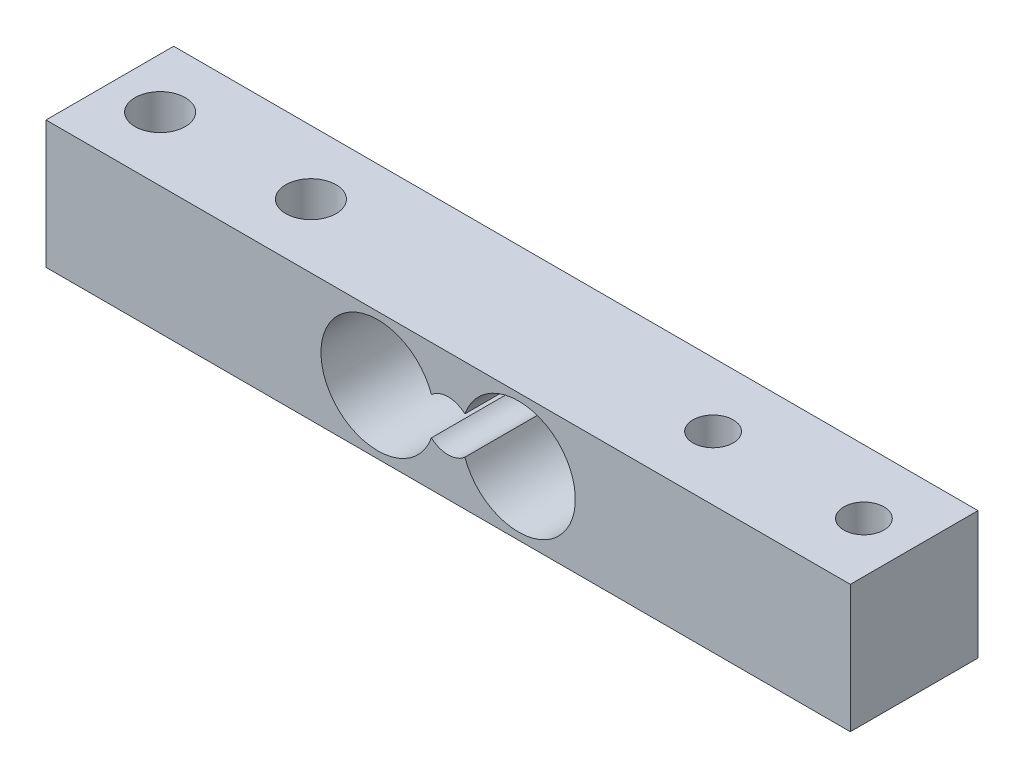
SolidWorks part; units mm, degrees
ref_plane "Front" through (0, 0, 0) normal (0, 0, 1) x (1, 0, 0)
ref_plane "Top" through (0, 0, 0) normal (0, 1, 0) x (1, 0, 0)
ref_plane "Right" through (0, 0, 0) normal (1, 0, 0) x (0, 0, -1)
sketch "Sketch1" plane through (0, 0, 0) normal (0, 1, 0) x (1, 0, 0)
  line L0 (-40, 0) -> (40, 0) construction
  line L1 (-40, -6.35) -> (40, -6.35)
  line L2 (-40, -6.35) -> (-40, 6.35)
  line L3 (-40, 6.35) -> (40, 6.35)
  line L4 (40, -6.35) -> (40, 6.35)
  line L5 (-40, -6.35) -> (40, 6.35) construction
  line L6 (-40, 6.35) -> (40, -6.35) construction
  circle A0 centre (-35, 0) radius 2.5
  circle A1 centre (-20, 0) radius 2.5
  circle A2 centre (20, 0) radius 2
  circle A3 centre (35, 0) radius 2
  point P0 (0, 0)
  dimension "D3" = 4
  dimension "D4" = 4
  dimension "D5" = 5
  dimension "D6" = 5
  dimension "D1" = 80
  dimension "D2" = 12.7
  dimension "D7" = 5
  dimension "D8" = 15
  dimension "D9" = 15
  dimension "D10" = 5
extrude "Boss-Extrude1" add sketch "Sketch1" along normal blind 12.7
sketch "Sketch2" plane through (0, 0, 6.35) normal (0, 0, 1) x (1, 0, 0)
  line L0 (-40, 6.35) -> (40, 6.35) construction
  line L1 (-40, 12.7) -> (-40, 0) construction
  line L2 (40, 12.7) -> (40, 0) construction
  line L3 (0, 12.7) -> (0, 0) construction
  line L4 (-40, 12.7) -> (40, 12.7) construction
  arc A0 (-1.6662, 8.2138) -> (-1.6662, 4.4862) centre (-7, 6.35) ccw
  arc A1 (1.6663, 4.4862) -> (1.6663, 8.2138) centre (7, 6.35) ccw
  arc A2 (-1.6662, 4.4862) -> (1.6663, 4.4862) centre (0, 6.35) ccw
  arc A3 (1.6663, 8.2138) -> (-1.6662, 8.2138) centre (0, 6.35) ccw
  point P15 (0, 6.35)
  dimension "D1" = 11.3
  dimension "D2" = 11.3
  dimension "D5" = 5
  dimension "D3" = 7
  dimension "D4" = 7
extrude "Cut-Extrude1" cut sketch "Sketch2" against normal through all
